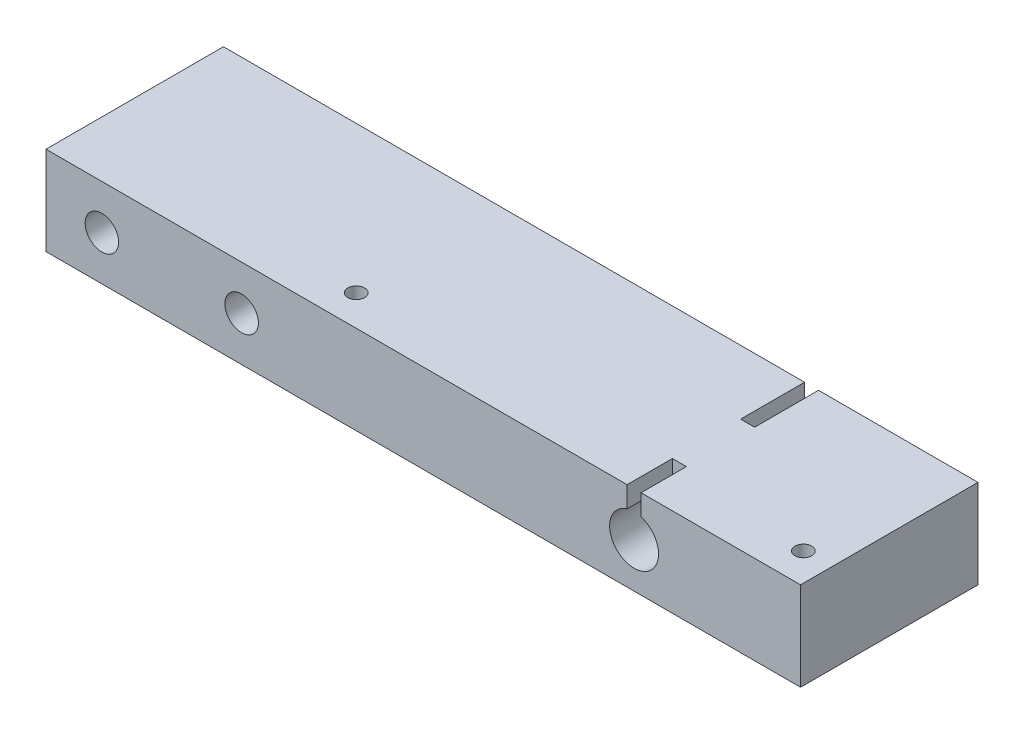
SolidWorks part; units mm, degrees
ref_plane "Front Plane" through (0, 0, 0) normal (0, 0, 1) x (1, 0, 0)
ref_plane "Top Plane" through (0, 0, 0) normal (0, 1, 0) x (1, 0, 0)
ref_plane "Right Plane" through (0, 0, 0) normal (1, 0, 0) x (0, 0, -1)
sketch "Sketch1" plane through (0, 0, 0) normal (0, 0, 1) x (1, 0, 0)
  line L1 (0, 0) -> (54, 0)
  line L2 (0, 0) -> (0, 6.35)
  line L3 (0, 6.35) -> (54, 6.35)
  line L4 (54, 0) -> (54, 6.35)
extrude "Boss-Extrude1" add sketch "Sketch1" along normal blind 12.7
sketch "Sketch3" plane through (0, 6.35, 0) normal (0, 1, 0) x (1, 0, 0)
  line L0 (42, -17.996) -> (42, 5.2833) construction
  line L2 (54, -6.35) -> (-1.1589, -6.35) construction
  line L3 (54, -12.7) -> (54, 0) construction
  line L4 (54, -12.7) -> (0, -12.7) construction
  line L5 (42.5877, -12.7) -> (41.5877, -12.7)
  line L6 (42.5877, -12.7) -> (42.5877, -9.4569)
  line L7 (42.5877, -9.4569) -> (41.5877, -9.4569)
  line L8 (41.5877, -12.7) -> (41.5877, -9.4569)
  line L10 (42.5877, 0) -> (41.5877, 0)
  line L11 (42.5877, 0) -> (42.5877, -4.5774)
  line L12 (42.5877, -4.5774) -> (41.5877, -4.5774)
  line L13 (41.5877, 0) -> (41.5877, -4.5774)
extrude "Cut-Extrude1" cut sketch "Sketch3" against normal blind 2
sketch "Sketch4" plane through (0, 0, 12.7) normal (0, 0, 1) x (1, 0, 0)
  line L0 (54, 3.175) -> (0, 3.175) construction
  line L1 (54, 0) -> (54, 6.35) construction
  line L2 (0, 6.35) -> (0, 0) construction
  line L3 (42.0877, 0) -> (42.0877, 6.35) construction
  line L4 (42.5877, 0) -> (41.5877, 0) construction
  line L5 (42.5877, 6.35) -> (41.5877, 6.35) construction
  circle A0 centre (42.0877, 3.175) radius 1.75
extrude "Cut-Extrude2" cut sketch "Sketch4" against normal through all
sketch "Sketch5" plane through (0, 6.35, 0) normal (0, 1, 0) x (1, 0, 0)
  line L0 (54, -10.5) -> (-2.4296, -10.5) construction
  line L1 (54, -12.7) -> (54, 0) construction
  line L2 (52, -19.5209) -> (52, 7.0115) construction
  circle A0 centre (52, -10.5) radius 0.6
  circle A1 centre (20, -10.5) radius 0.6
  dimension "D1" = 32
extrude "Cut-Extrude3" cut sketch "Sketch5" against normal through all
sketch "Sketch6" plane through (0, 0, 12.7) normal (0, 0, 1) x (1, 0, 0)
  line L0 (54, 3.175) -> (0, 3.175) construction
  line L1 (54, 0) -> (54, 6.35) construction
  line L2 (0, 6.35) -> (0, 0) construction
  line L3 (4, 0) -> (4, 6.35) construction
  line L4 (0, 0) -> (54, 0) construction
  line L5 (41.5877, 6.35) -> (0, 6.35) construction
  circle A0 centre (4, 3.175) radius 1.2
  circle A1 centre (14, 3.175) radius 1.2
  dimension "D1" = 10
extrude "Cut-Extrude4" cut sketch "Sketch6" against normal through all
sketch "Sketch10" plane through (0, 6.35, 0) normal (0, 1, 0) x (1, 0, 0)
  line L0 (54, -6.35) -> (0, -6.35) construction
  line L1 (54, -12.7) -> (54, 0) construction
  line L2 (0, -12.7) -> (0, 0) construction
  line L3 (42.0877, 0) -> (42.0877, -12.7) construction
  line L4 (43.8377, 0) -> (40.3377, 0) construction
  line L5 (40.3377, -12.7) -> (43.8377, -12.7) construction
  line L6 (42.0877, -6.35) -> (36.2418, -12.7) construction
  line L7 (41.5877, -12.7) -> (0, -12.7) construction
  line L8 (42.0877, -6.35) -> (50.7905, -12.7) construction
  line L9 (54, -12.7) -> (42.5877, -12.7) construction
ref_plane "Plane6" through (25.9446, 0, 23.8851) normal (-0.7357, 0, -0.6773) x (-0.6773, 0, 0.7357)
sketch "Sketch12" plane through (25.9446, 0, 23.8851) normal (-0.7357, 0, -0.6773) x (-0.6773, 0, 0.7357)
  line L0 (-23.8344, 6.35) -> (-20.3806, -3.6111) construction
  circle A0 centre (-22.3994, 2.2113) radius 0.6
extrude "Cut-Extrude6" cut sketch "Sketch12" along normal blind 15
